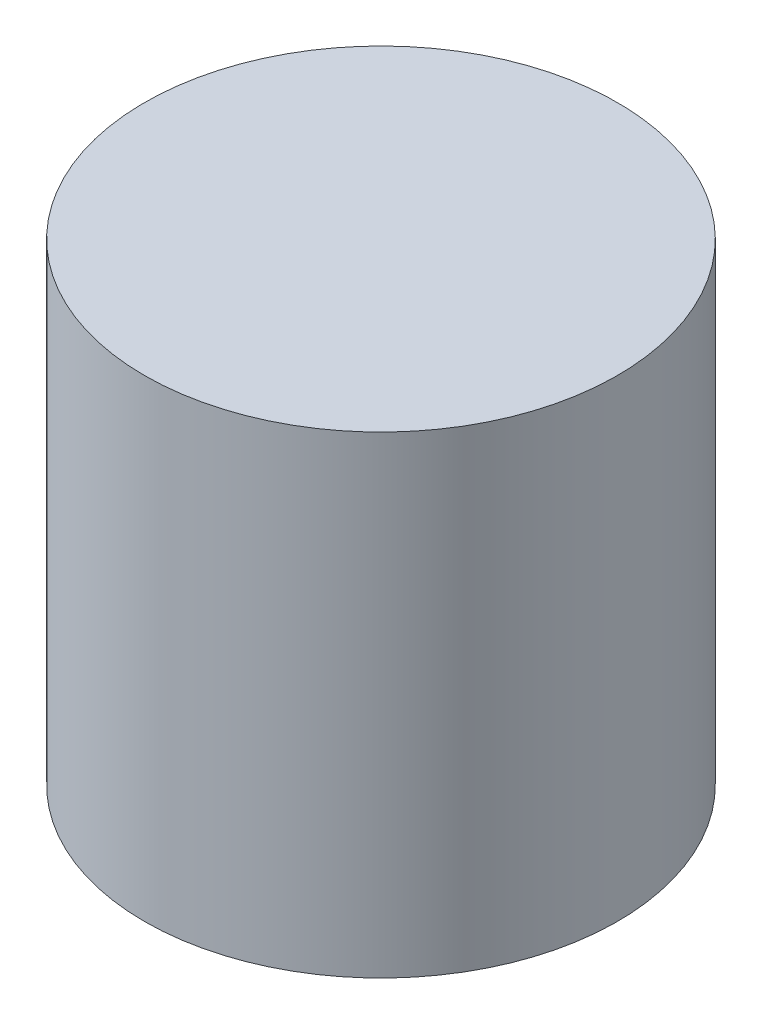
SolidWorks part; units mm, degrees
ref_plane "前视基准面" through (0, 0, 0) normal (0, 0, 1) x (1, 0, 0)
ref_plane "上视基准面" through (0, 0, 0) normal (0, 1, 0) x (1, 0, 0)
ref_plane "右视基准面" through (0, 0, 0) normal (1, 0, 0) x (0, 0, -1)
other "Configuration Table"
sketch "草图1" plane through (0, 0, 0) normal (0, 1, 0) x (1, 0, 0)
  circle A0 centre (0, 0) radius 1
  dimension "D1" = 2
extrude "凸台-拉伸1" add sketch "草图1" along normal blind 2
